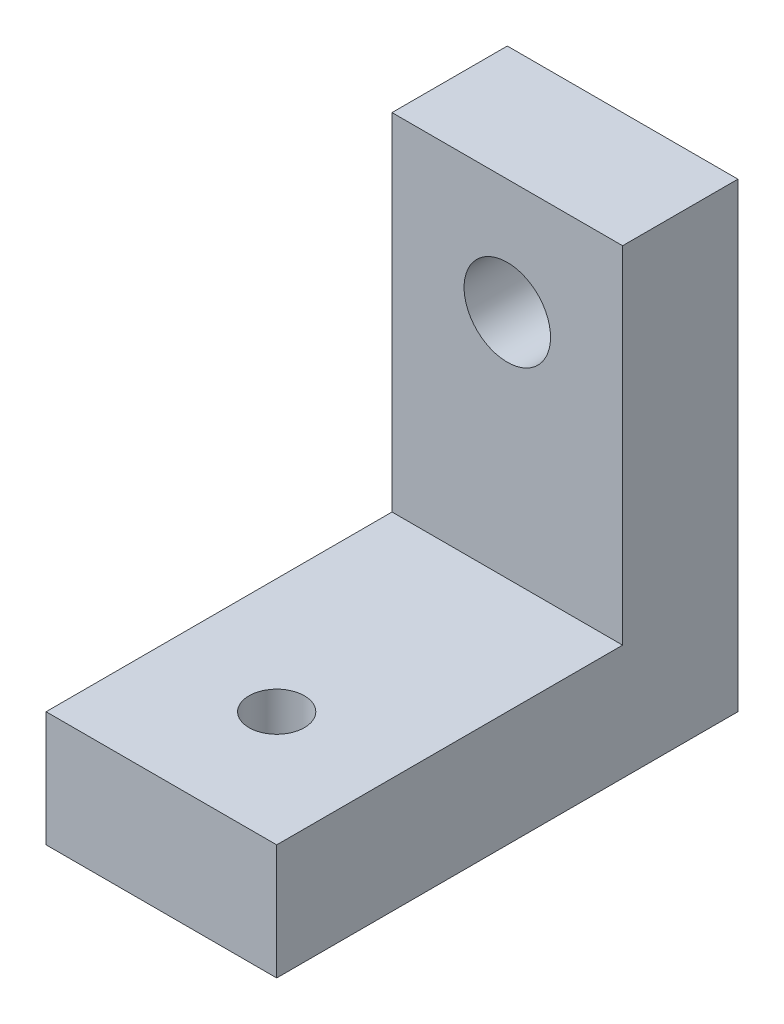
SolidWorks part; units mm, degrees
ref_plane "Front Plane" through (0, 0, 0) normal (0, 0, 1) x (1, 0, 0)
ref_plane "Top Plane" through (0, 0, 0) normal (0, 1, 0) x (1, 0, 0)
ref_plane "Right Plane" through (0, 0, 0) normal (1, 0, 0) x (0, 0, -1)
sketch "Sketch1" plane through (0, 0, 0) normal (0, 0, 1) x (1, 0, 0)
  line L0 (-6.35, 0) -> (-6.35, -19.05)
  line L1 (-6.35, -19.05) -> (6.35, -19.05)
  line L2 (6.35, -19.05) -> (6.35, 0)
  line L5 (-6.35, 0) -> (-6.35, 6.35)
  line L6 (-6.35, 6.35) -> (6.35, 6.35)
  line L7 (6.35, 0) -> (6.35, 6.35)
  circle A1 centre (0, 0) radius 2.3813
  dimension "D1" = 12.7
  dimension "D2" = 4.7625
  dimension "D3" = 25.4
  dimension "D4" = 19.05
extrude "Boss-Extrude1" add sketch "Sketch1" along normal blind 6.35
sketch "Sketch2" plane through (0, 0, 6.35) normal (0, 0, 1) x (1, 0, 0)
  line L0 (6.35, -19.05) -> (6.35, 6.35) construction
  line L1 (-6.35, -19.05) -> (6.35, -19.05)
  line L2 (-6.35, -19.05) -> (-6.35, -12.7)
  line L3 (-6.35, -12.7) -> (6.35, -12.7)
  line L4 (6.35, -19.05) -> (6.35, -12.7)
  dimension "D1" = 6.35
extrude "Boss-Extrude2" add sketch "Sketch2" along normal blind 19.05
sketch "Sketch3" plane through (0, -12.7, 0) normal (0, 1, 0) x (1, 0, 0)
  line L0 (-6.35, -25.4) -> (-6.35, -6.35) construction
  line L1 (6.35, -25.4) -> (-6.35, -25.4) construction
  circle A0 centre (0, -19.05) radius 1.524
  dimension "D1" = 3.048
  dimension "D2" = 6.35
  dimension "D3" = 6.35
extrude "Cut-Extrude1" cut sketch "Sketch3" against normal blind 19.05
